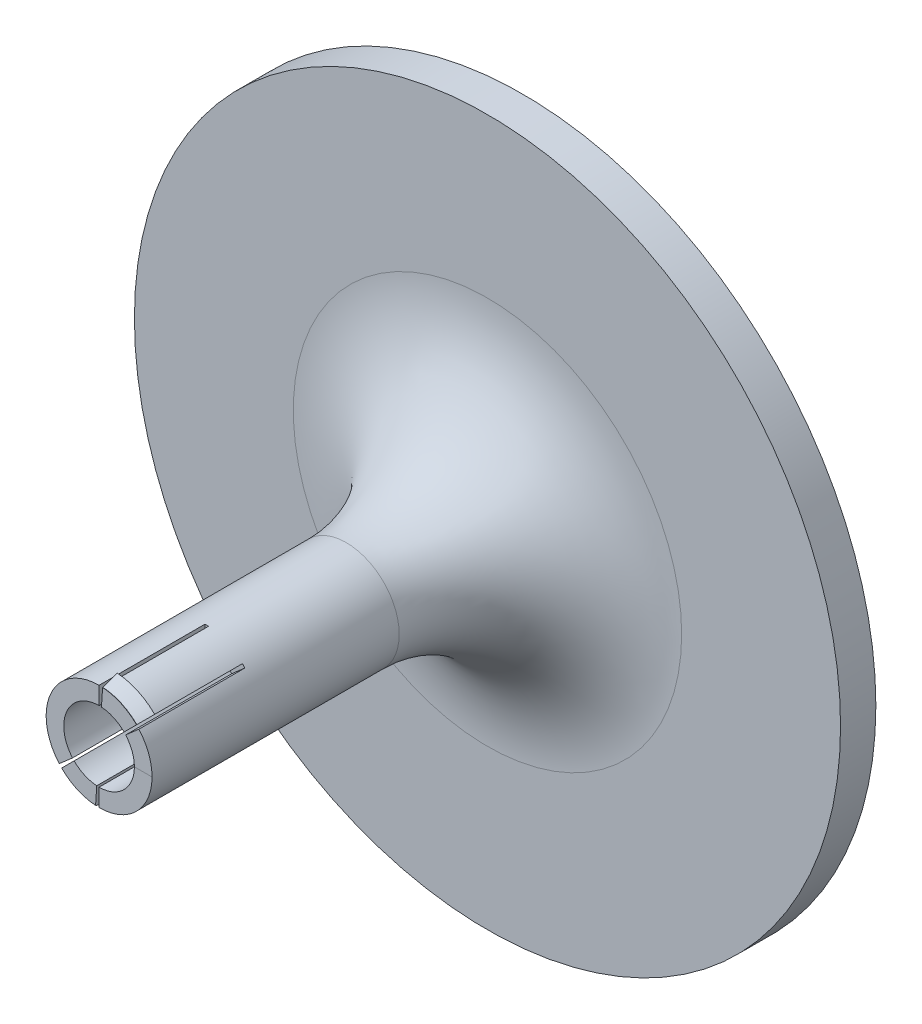
SolidWorks part; units mm, degrees
ref_plane "前视基准面" through (0, 0, 0) normal (0, 0, 1) x (1, 0, 0)
ref_plane "上视基准面" through (0, 0, 0) normal (0, 1, 0) x (1, 0, 0)
ref_plane "右视基准面" through (0, 0, 0) normal (1, 0, 0) x (0, 0, -1)
sketch "草图1" plane through (0, 0, 0) normal (0, 1, 0) x (1, 0, 0)
  line L0 (0, 0) -> (7.5, 0)
  line L1 (0, 0) -> (0, 60)
  line L2 (0, 60) -> (50, 60)
  line L3 (50, 60) -> (50, 55)
  line L4 (50, 55) -> (27.5, 55)
  line L5 (7.5, 35) -> (7.5, 0)
  arc A0 (27.5, 55) -> (7.5, 35) centre (27.5, 35) ccw
  dimension "D2" = 60
  dimension "D5" = 20
  dimension "D1" = 7.5
  dimension "D3" = 50
  dimension "D4" = 5
sketch "草图2" plane through (0, 0, 0) normal (0, 0, 1) x (1, 0, 0)
  circle A0 centre (0, 0) radius 50
sweep "扫描1" add profiles "草图1" path "草图2"
sketch "草图3" plane through (0, 0, 0) normal (0, 0, 1) x (1, 0, 0)
  circle A0 centre (0, 0) radius 5
  dimension "D1" = 10
extrude "切除-拉伸1" cut sketch "草图3" against normal through all
sketch "草图5" plane through (0, 0, 0) normal (0, 0, 1) x (1, 0, 0)
  line L10 (0, 7.5) -> (0.5, 7.5)
  line L17 (0, 0) -> (0.5, 7.5)
  line L21 (0, 0) -> (0, 7.5)
  circle A3 centre (0, 0) radius 7.5 construction
  circle A4 centre (0, 0) radius 7.5 construction
  dimension "D1" = 0.5
extrude "切除-拉伸2" cut sketch "草图5" against normal blind 15
sketch "草图6" plane through (0, 0, 0) normal (0, 0, 1) x (1, 0, 0)
  line L0 (0, 0) -> (5.3033, 5.3033)
  line L1 (5.3033, 5.3033) -> (5.6569, 4.9497)
  line L2 (0, 0) -> (5.6569, 4.9497)
  arc A0 (7.5, 0) -> (0.4989, 7.4834) centre (0, 0) ccw construction
  dimension "D1" = 0.5
extrude "切除-拉伸3" cut sketch "草图6" against normal blind 15
sketch "草图8" plane through (0, 0, 0) normal (0, 0, 1) x (1, 0, 0)
  line L0 (0, 0) -> (0, -7.5)
  line L1 (0.4989, 7.4834) -> (0, 0) construction
  line L2 (0, 0) -> (-0.4989, -7.4834)
  arc A0 (-0.4989, -7.4834) -> (0, -7.5) centre (0, 0) ccw
extrude "切除-拉伸4" cut sketch "草图8" against normal blind 15
sketch "草图9" plane through (0, 0, 0) normal (0, 0, 1) x (1, 0, 0)
  line L0 (3.5355, 3.5355) -> (0, 0) construction
  line L1 (0, 0) -> (-5.3033, -5.3033)
  line L2 (3.7629, 3.2925) -> (0, 0) construction
  line L3 (0, 0) -> (-5.6443, -4.9388)
  arc A0 (0, 7.5) -> (-0.4989, -7.4834) centre (0, 0) ccw construction
  arc A1 (-5.6443, -4.9388) -> (-5.3033, -5.3033) centre (0, 0) ccw
extrude "切除-拉伸5" cut sketch "草图9" against normal blind 15
sketch "草图10" plane through (0, 0, 0) normal (-0.9978, 0.0665, 0) x (0, 0, 1)
  line L0 (0, 7.4834) -> (-1.9999, 7.5)
  line L1 (0, 7.5) -> (-15, 7.5) construction
  line L2 (-1.9999, 7.5) -> (-1.9999, 8.3)
  line L3 (-1.9999, 8.3) -> (0, 7.4834)
  dimension "D1" = 2
  dimension "D2" = 0.8
sweep "扫描2" add profiles "草图10" path edge at (3.0991, 6.8297, 0)
sketch "草图11" plane through (0, 0, 0) normal (0.9978, -0.0665, 0) x (0, 0, -1)
  line L0 (0, -7.5) -> (2, -7.5)
  line L1 (15, -7.5) -> (0, -7.5) construction
  line L2 (2, -7.5) -> (2, -8.3)
  line L3 (2, -8.3) -> (0, -7.5)
  dimension "D1" = 2
  dimension "D2" = 0.8
sweep "扫描3" add profiles "草图11" path edge at (-3.0991, -6.8297, 0)
